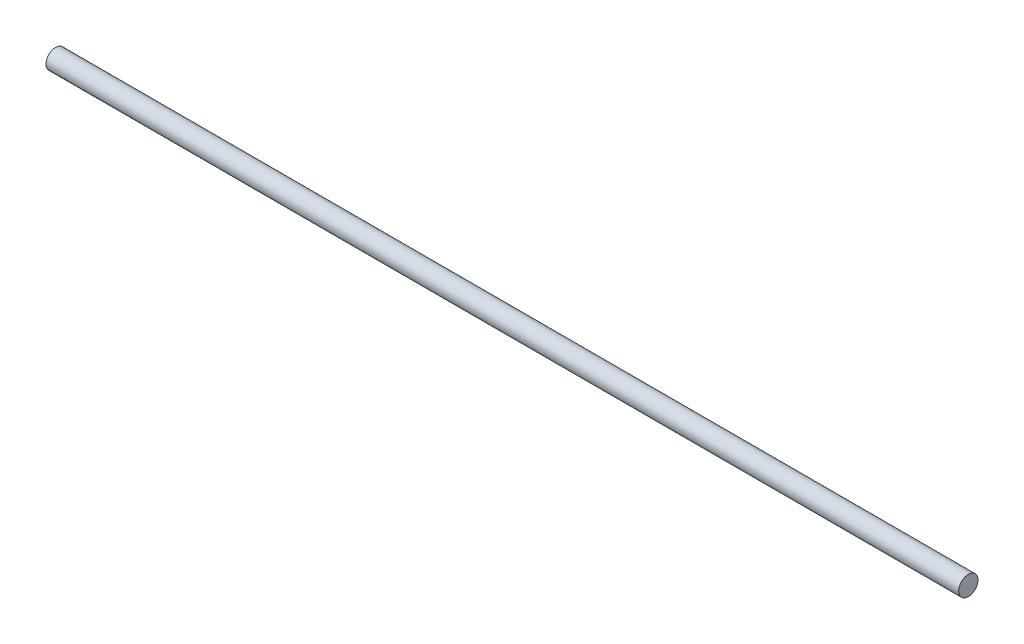
SolidWorks part; units mm, degrees
material "Alloy Steel (SS)"
ref_plane "Front Plane" through (0, 0, 0) normal (0, 0, 1) x (1, 0, 0)
ref_plane "Top Plane" through (0, 0, 0) normal (0, 1, 0) x (1, 0, 0)
ref_plane "Right Plane" through (0, 0, 0) normal (1, 0, 0) x (0, 0, -1)
sketch "Sketch1" plane through (0, 0, 0) normal (1, 0, 0) x (0, 0, -1)
  circle A0 centre (0, 0) radius 3.175
  dimension "D1" = 6.35
extrude "Boss-Extrude1" add sketch "Sketch1" along normal mid plane 299.974
